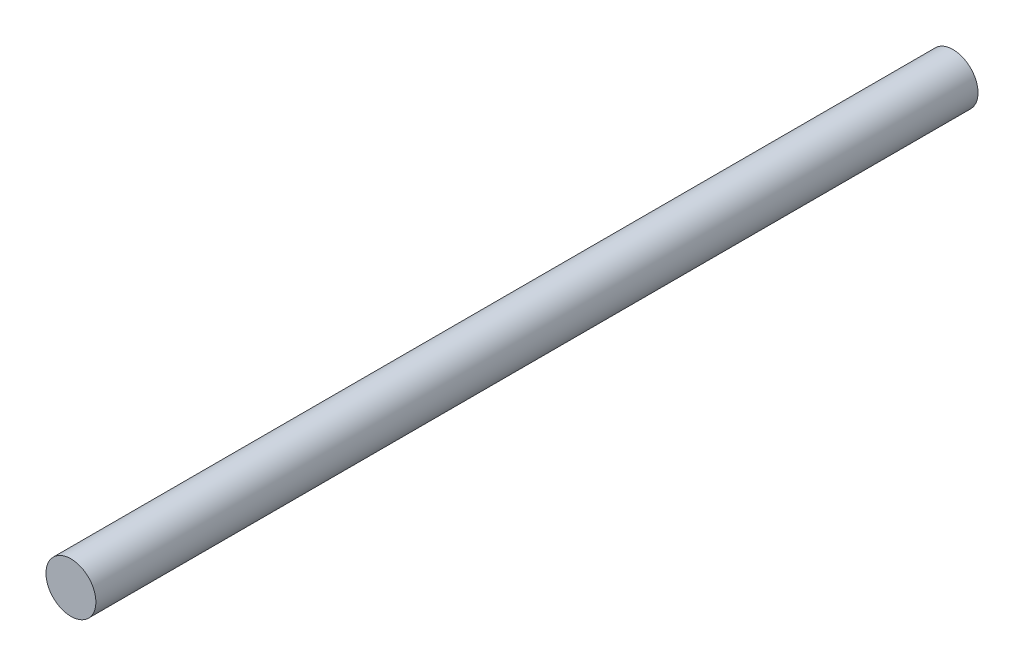
SolidWorks part; units mm, degrees
ref_plane "Front Plane" through (0, 0, 0) normal (0, 0, 1) x (1, 0, 0)
ref_plane "Top Plane" through (0, 0, 0) normal (0, 1, 0) x (1, 0, 0)
ref_plane "Right Plane" through (0, 0, 0) normal (1, 0, 0) x (0, 0, -1)
sketch "Sketch1" plane through (0, 0, 0) normal (0, 0, 1) x (1, 0, 0)
  circle A0 centre (0, 0) radius 3
  dimension "D1" = 6
extrude "Boss-Extrude1" add sketch "Sketch1" along normal blind 106
